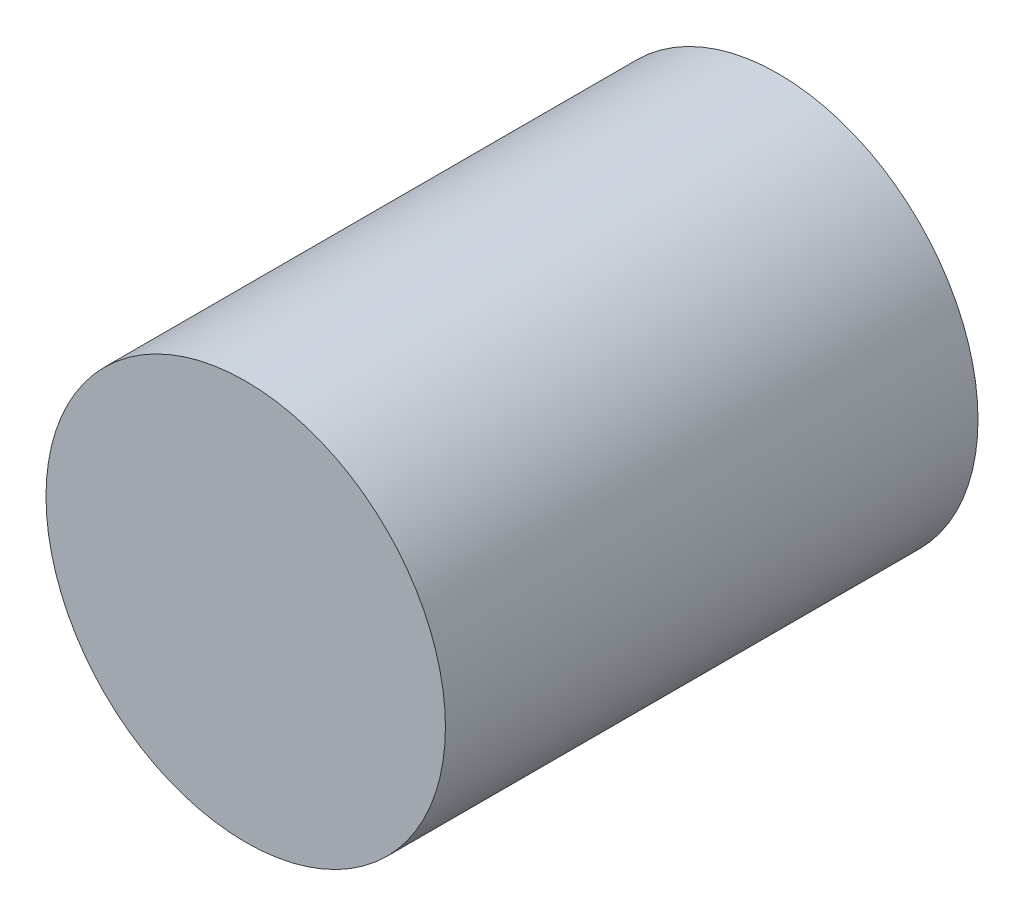
SolidWorks part; units mm, degrees
ref_plane "前视基准面" through (0, 0, 0) normal (0, 0, 1) x (1, 0, 0)
ref_plane "上视基准面" through (0, 0, 0) normal (0, 1, 0) x (1, 0, 0)
ref_plane "右视基准面" through (0, 0, 0) normal (1, 0, 0) x (0, 0, -1)
sketch "草图1" plane through (0, 0, 0) normal (0, 0, 1) x (1, 0, 0)
  circle A0 centre (0, 0) radius 30
  dimension "D1" = 60
extrude "凸台-拉伸1" add sketch "草图1" along normal blind 80
